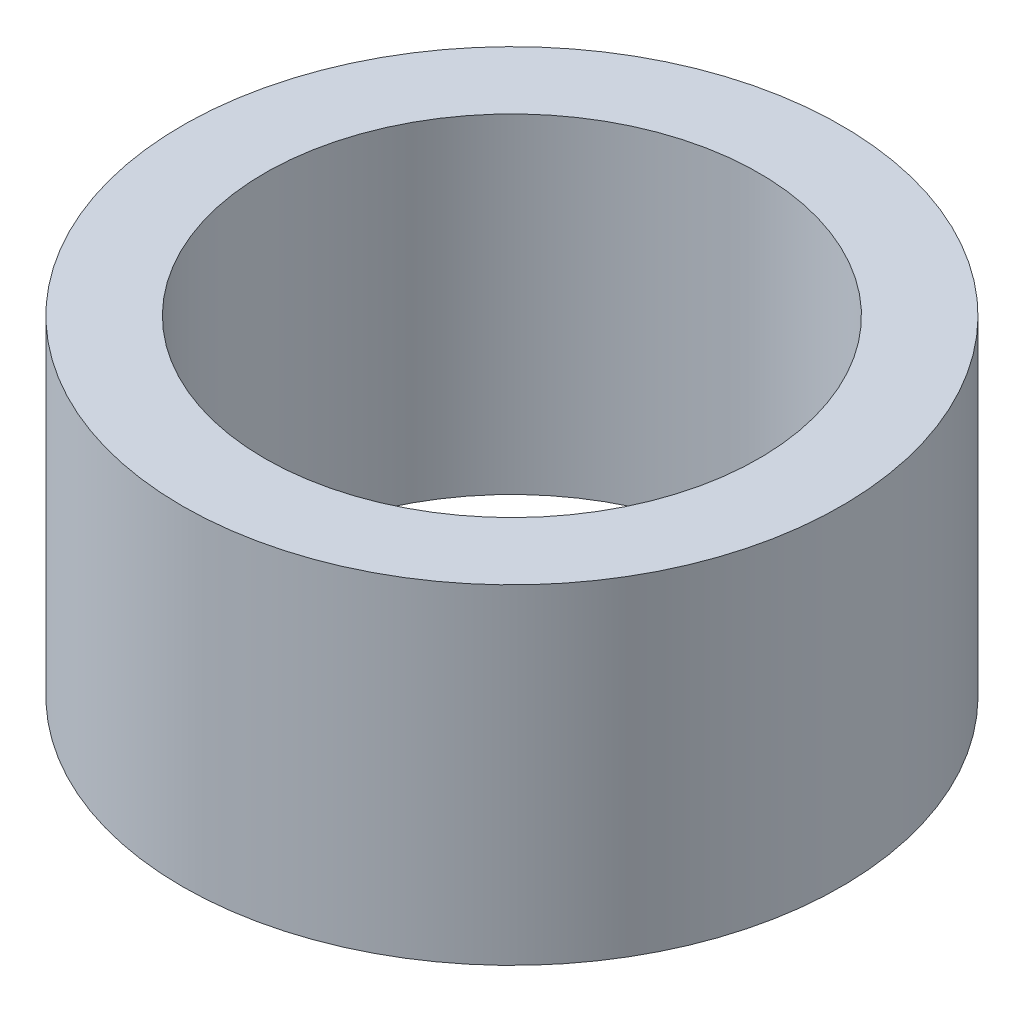
SolidWorks part; units mm, degrees
ref_plane "Front Plane" through (0, 0, 0) normal (0, 0, 1) x (1, 0, 0)
ref_plane "Top Plane" through (0, 0, 0) normal (0, 1, 0) x (1, 0, 0)
ref_plane "Right Plane" through (0, 0, 0) normal (1, 0, 0) x (0, 0, -1)
sketch "Sketch1" plane through (0, 0, 0) normal (0, 1, 0) x (1, 0, 0)
  circle A0 centre (0, 0) radius 20
  circle A1 centre (0, 0) radius 15
  dimension "D1" = 40
  dimension "D2" = 30
extrude "Boss-Extrude1" add sketch "Sketch1" along normal blind 20
